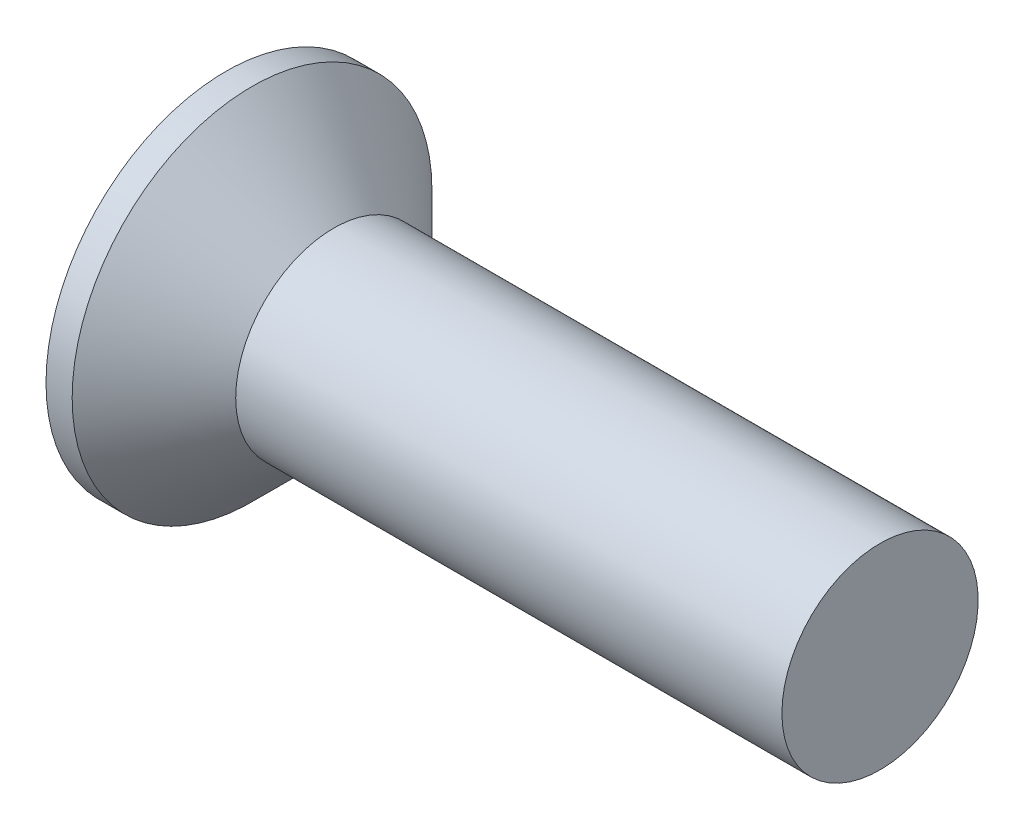
SolidWorks part; units mm, degrees
ref_plane "Plan de face" through (0, 0, 0) normal (0, 0, 1) x (1, 0, 0)
ref_plane "Plan de dessus" through (0, 0, 0) normal (0, 1, 0) x (1, 0, 0)
ref_plane "Plan de droite" through (0, 0, 0) normal (1, 0, 0) x (0, 0, -1)
sketch "Esquisse1" plane through (0, 0, 0) normal (0, 0, 1) x (1, 0, 0)
  line L0 (0, 0) -> (10, 0)
  line L1 (10, 0) -> (10, 1.5)
  line L2 (10, 1.5) -> (1.65, 1.5)
  line L4 (0, 2.75) -> (0, 0)
  line L5 (0, 2.75) -> (0.4, 2.75)
  line L6 (0.4, 2.75) -> (1.65, 1.5)
  dimension "D1" = 10
  dimension "D2" = 1.5
  dimension "D3" = 2.75
  dimension "D4" = 1.65
  dimension "D5" = 45
revolve "Révolution1" add sketch "Esquisse1" angle 360 about L0
equation "\"D3@Esquisse1\"=5.5/2"
